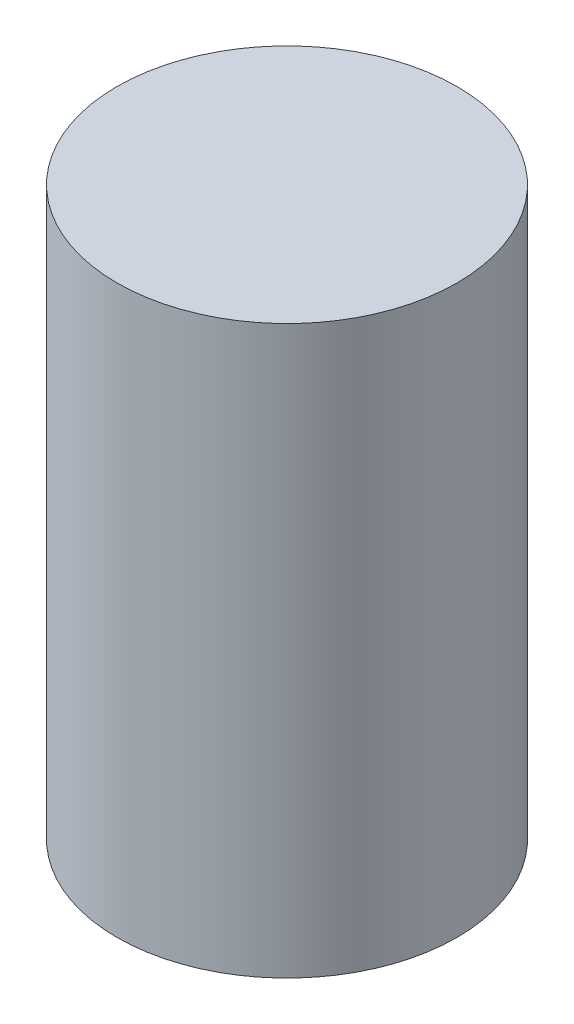
SolidWorks part; units mm, degrees
material "1023 Carbon Steel Sheet (SS)"
ref_plane "Front Plane" through (0, 0, 0) normal (0, 0, 1) x (1, 0, 0)
ref_plane "Top Plane" through (0, 0, 0) normal (0, 1, 0) x (1, 0, 0)
ref_plane "Right Plane" through (0, 0, 0) normal (1, 0, 0) x (0, 0, -1)
sketch "Sketch1" plane through (0, 0, 0) normal (0, 1, 0) x (1, 0, 0)
  circle A0 centre (0, 0) radius 30
  dimension "D1" = 60
extrude "Boss-Extrude1" add sketch "Sketch1" along normal blind 100
sketch "Sketch2" plane through (0, 100, 0) normal (0, 1, 0) x (1, 0, 0)
  line L0 (0, 30) -> (0, -30) construction
  circle A1 centre (0, 0) radius 30 construction
